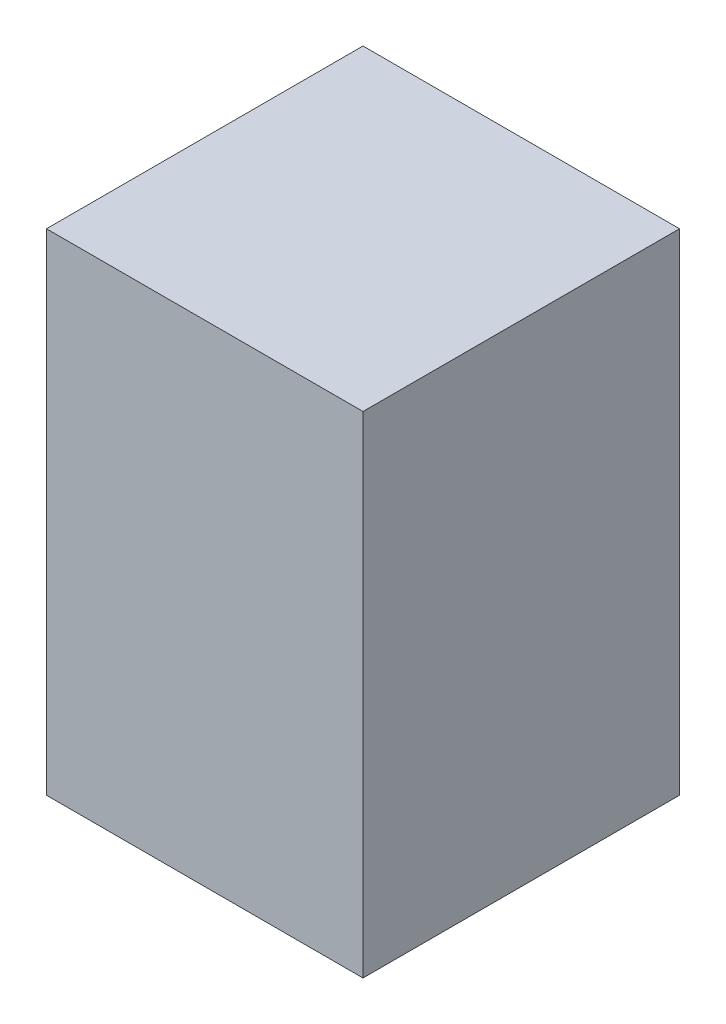
SolidWorks part; units mm, degrees
ref_plane "Front" through (0, 0, 0) normal (0, 0, 1) x (1, 0, 0)
ref_plane "Top" through (0, 0, 0) normal (0, 1, 0) x (1, 0, 0)
ref_plane "Right" through (0, 0, 0) normal (1, 0, 0) x (0, 0, -1)
sketch "Sketch1" plane through (0, 0, 0) normal (0, 1, 0) x (1, 0, 0)
  line L1 (-100, -100) -> (100, -100)
  line L2 (-100, -100) -> (-100, 100)
  line L3 (-100, 100) -> (100, 100)
  line L4 (100, -100) -> (100, 100)
  line L5 (-100, -100) -> (100, 100) construction
  line L6 (-100, 100) -> (100, -100) construction
  point P0 (0, 0)
  dimension "D1" = 200
  dimension "D2" = 200
extrude "Boss-Extrude1" add sketch "Sketch1" along normal blind 310
